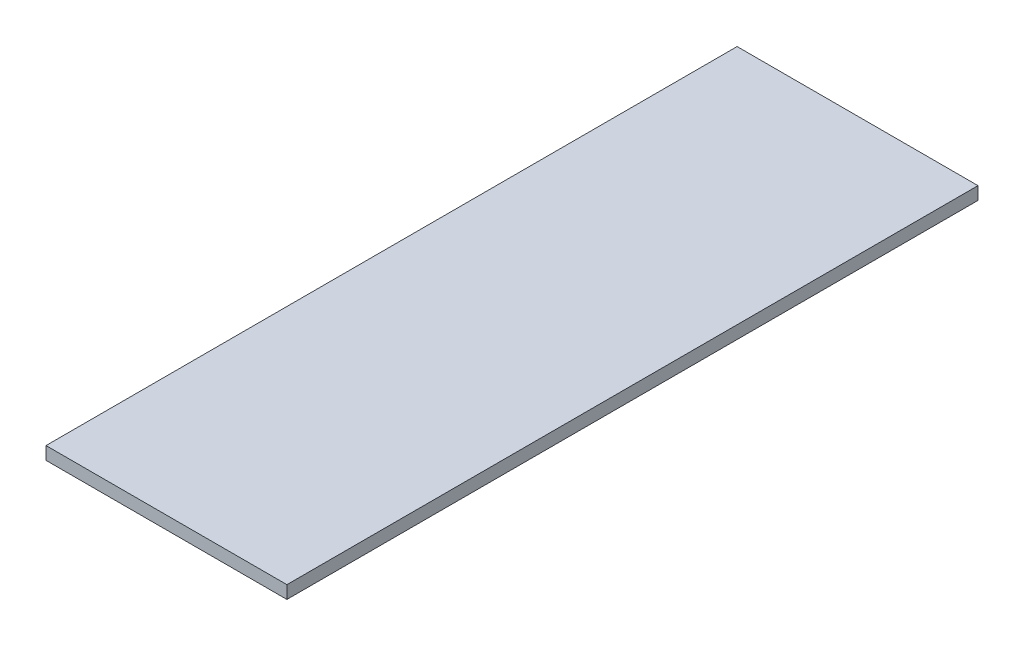
SolidWorks part; units mm, degrees
ref_plane "Front Plane" through (0, 0, 0) normal (0, 0, 1) x (1, 0, 0)
ref_plane "Top Plane" through (0, 0, 0) normal (0, 1, 0) x (1, 0, 0)
ref_plane "Right Plane" through (0, 0, 0) normal (1, 0, 0) x (0, 0, -1)
sketch "Sketch1" plane through (0, 0, 0) normal (0, 1, 0) x (1, 0, 0)
  line L1 (0, 0) -> (122, 0)
  line L2 (0, 0) -> (0, 350)
  line L3 (0, 350) -> (122, 350)
  line L4 (122, 0) -> (122, 350)
  dimension "H" = 350
  dimension "L" = 122
extrude "Boss-Extrude1" add sketch "Sketch1" along normal blind 6.5
sketch "Sketch2" plane through (0, 6.5, 0) normal (0, 1, 0) x (1, 0, 0)
  line L0 (-7, 350) -> (-7, 201)
  line L1 (-7, 201) -> (122, 201)
  line L4 (0, 350) -> (0, 0)
  line L5 (0, 0) -> (122, 0)
  line L6 (122, 0) -> (122, 350)
  line L7 (122, 350) -> (0, 350)
  line L8 (0, 350) -> (0, 0)
  line L9 (0, 0) -> (122, 0)
  line L10 (122, 0) -> (122, 350)
  line L11 (122, 350) -> (0, 350)
  line M9 (122, 0) -> (122, 350)
  line M10 (122, 350) -> (0, 350)
  dimension "D2" = 129
  dimension "D3" = 149
  dimension "D1" = 0
extrude "Cut-Extrude1" [suppressed] cut sketch "Sketch2" against normal through all contours L0 L1 M9 M10
